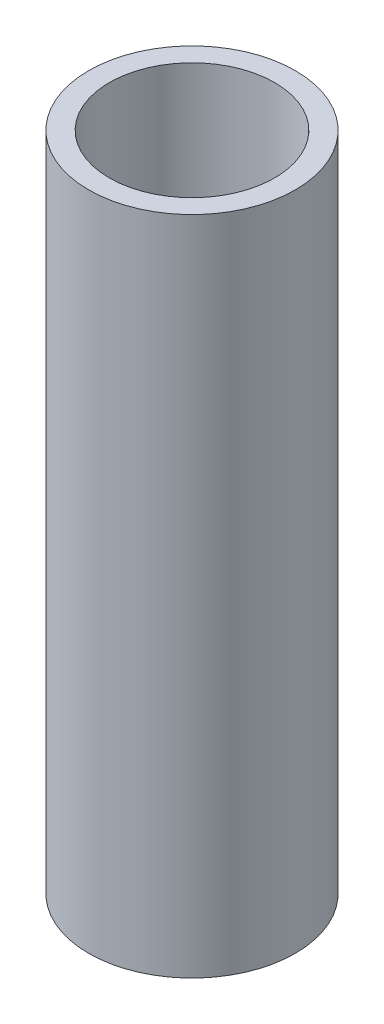
SolidWorks part; units mm, degrees
ref_plane "Front Plane" through (0, 0, 0) normal (0, 0, 1) x (1, 0, 0)
ref_plane "Top Plane" through (0, 0, 0) normal (0, 1, 0) x (1, 0, 0)
ref_plane "Right Plane" through (0, 0, 0) normal (1, 0, 0) x (0, 0, -1)
sketch "Sketch1" plane through (0, 0, 0) normal (0, 1, 0) x (1, 0, 0)
  circle A0 centre (0, 0) radius 1.25
  circle A1 centre (0, 0) radius 1
extrude "Boss-Extrude1" add sketch "Sketch1" along normal blind 8
